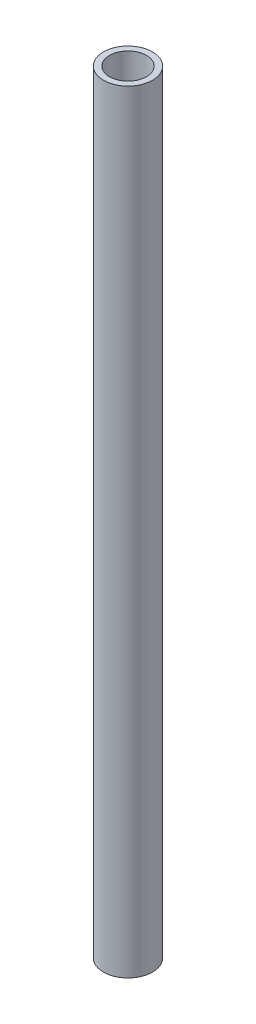
SolidWorks part; units mm, degrees
ref_plane "Płaszczyzna przednia" through (0, 0, 0) normal (0, 0, 1) x (1, 0, 0)
ref_plane "Płaszczyzna górna" through (0, 0, 0) normal (0, 1, 0) x (1, 0, 0)
ref_plane "Płaszczyzna prawa" through (0, 0, 0) normal (1, 0, 0) x (0, 0, -1)
sketch "Szkic1" plane through (0, 0, 0) normal (0, 1, 0) x (1, 0, 0)
  circle A0 centre (0, 0) radius 12.7
  circle A1 centre (0, 0) radius 16.85
  dimension "D1" = 25.4
  dimension "D2" = 33.7
extrude "Dodanie-wyciągnięcie1" add sketch "Szkic1" along normal blind 530
